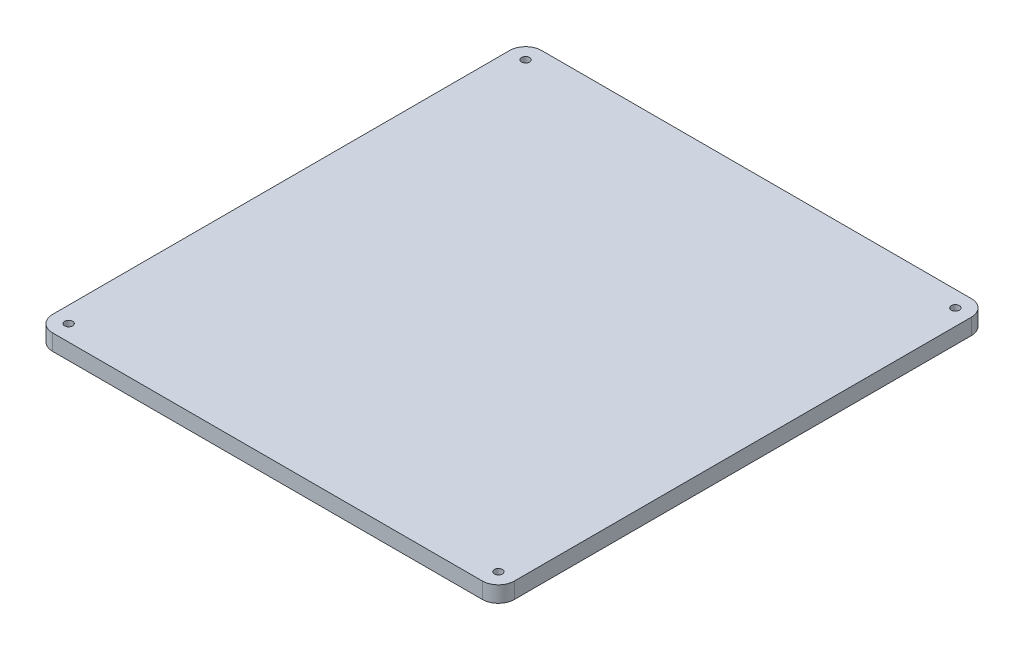
SolidWorks part; units mm, degrees
ref_plane "Front Plane" through (0, 0, 0) normal (0, 0, 1) x (1, 0, 0)
ref_plane "Top Plane" through (0, 0, 0) normal (0, 1, 0) x (1, 0, 0)
ref_plane "Right Plane" through (0, 0, 0) normal (1, 0, 0) x (0, 0, -1)
sketch "Sketch1" plane through (0, 0, 0) normal (0, 1, 0) x (1, 0, 0)
  line L0 (78.3009, 56.6557) -> (78.3009, -248.3443) construction
  line L1 (-65.6991, 56.6557) -> (222.3009, 56.6557)
  line L2 (-65.6991, 56.6557) -> (-65.6991, -248.3443)
  line L3 (-65.6991, -248.3443) -> (222.3009, -248.3443)
  line L4 (222.3009, 56.6557) -> (222.3009, -248.3443)
  line L5 (-65.6991, -95.8443) -> (222.3009, -95.8443) construction
  circle A8 centre (-55.6991, 46.6557) radius 2.5
  circle A9 centre (212.3009, 46.6557) radius 2.5
  circle A10 centre (212.3009, -238.3443) radius 2.5
  circle A11 centre (-55.6991, -238.3443) radius 2.5
  dimension "D8" = 5
  dimension "D9" = 10
  dimension "D10" = 10
  dimension "D1" = 288
  dimension "D2" = 305
extrude "Boss-Extrude1" add sketch "Sketch1" along normal blind 10
fillet "Fillet1" radius 10 4 edges at (-65.6991, 5, 248.3443) (222.3009, 5, 248.3443) (222.3009, 5, -56.6557) (-65.6991, 5, -56.6557)
